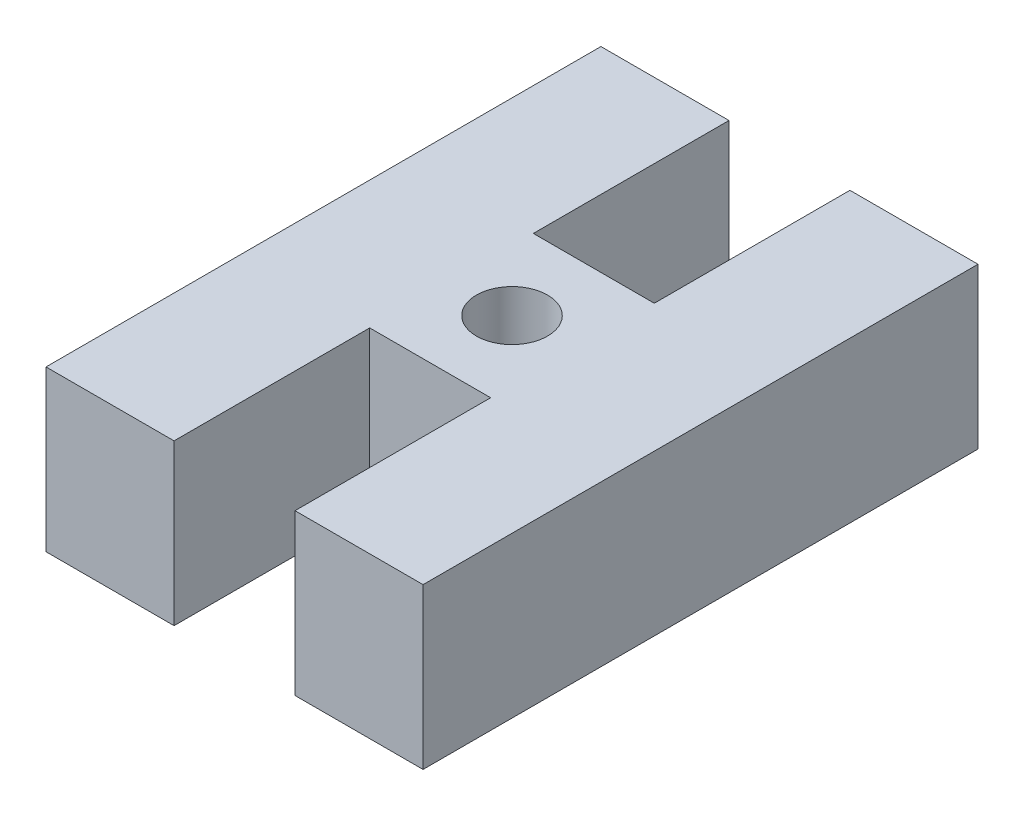
SolidWorks part; units mm, degrees
ref_plane "Plan de face" through (0, 0, 0) normal (0, 0, 1) x (1, 0, 0)
ref_plane "Plan de dessus" through (0, 0, 0) normal (0, 1, 0) x (1, 0, 0)
ref_plane "Plan de droite" through (0, 0, 0) normal (1, 0, 0) x (0, 0, -1)
sketch "Esquisse1" plane through (0, 0, 0) normal (0, 1, 0) x (1, 0, 0)
  line L0 (-6.6256, 0) -> (0, 0) construction
  line L1 (-5.5, -8) -> (-5.5, 8)
  line L2 (-5.5, 8) -> (-1.5, 8)
  line L3 (-1.5, 8) -> (-1.5, 2.5)
  line L4 (-1.5, 2.5) -> (1.5, 2.5)
  line L5 (1.5, 2.5) -> (1.5, 8)
  line L6 (1.5, 8) -> (5.5, 8)
  line L7 (5.5, 8) -> (5.5, -8)
  line L8 (1.5, -8) -> (5.5, -8)
  line L9 (1.5, -2.5) -> (1.5, -8)
  line L10 (-1.5, -2.5) -> (1.5, -2.5)
  line L11 (-1.5, -8) -> (-1.5, -2.5)
  line L12 (-5.5, -8) -> (-1.5, -8)
  line L13 (-5.3, -7.8) -> (-5.3, 7.8)
  line L14 (-5.3, 7.8) -> (-1.7, 7.8)
  line L15 (-1.7, 7.8) -> (-1.7, 2.3)
  line L16 (-1.7, 2.3) -> (1.7, 2.3)
  line L17 (1.7, 2.3) -> (1.7, 7.8)
  line L18 (1.7, 7.8) -> (5.3, 7.8)
  line L19 (5.3, 7.8) -> (5.3, -7.8)
  line L20 (1.7, -7.8) -> (5.3, -7.8)
  line L21 (1.7, -2.3) -> (1.7, -7.8)
  line L22 (-1.7, -2.3) -> (1.7, -2.3)
  line L23 (-1.7, -7.8) -> (-1.7, -2.3)
  line L24 (-5.3, -7.8) -> (-1.7, -7.8)
  point P5 (0, 2.5)
  point P14 (5.5, 0)
  point P15 (-5.5, 0)
  dimension "D1" = 16
  dimension "D2" = 11
  dimension "D3" = 5
  dimension "D4" = 3
  dimension "D5" = 0.2
extrude "Boss.-Extru.1" add sketch "Esquisse1" along normal blind 4.5 contours L13 L14 L15 L16 L17 L18 L19 L20 L21 L22 L23 L24
sketch "Esquisse2" plane through (0, 4.5, 0) normal (0, 1, 0) x (1, 0, 0)
  circle A0 centre (0, 0) radius 1
  dimension "D1" = 2
extrude "Enlèv. mat.-Extru.1" cut sketch "Esquisse2" against normal through all
